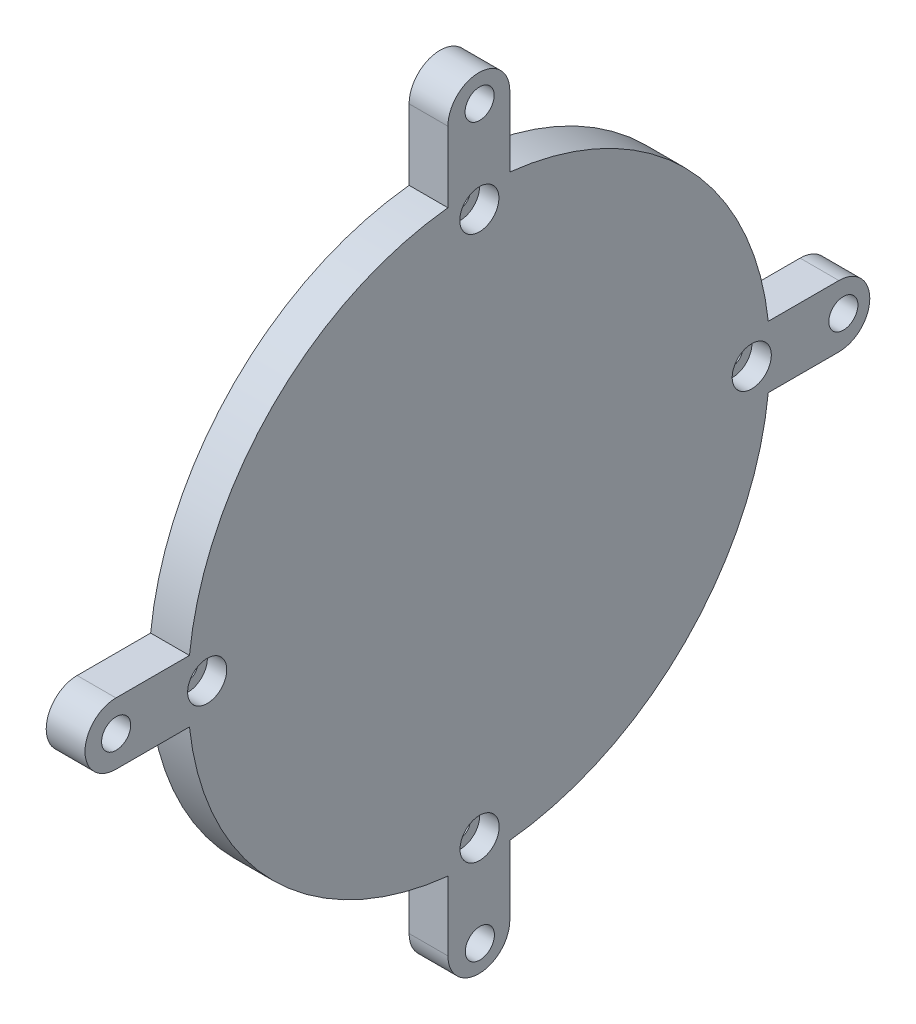
SolidWorks part; units mm, degrees
ref_plane "Front Plane" through (0, 0, 0) normal (1, 0, 0) x (0, 1, 0)
ref_plane "Top Plane" through (0, 0, 0) normal (0, 0, 1) x (0, 1, 0)
ref_plane "Right Plane" through (0, 0, 0) normal (0, 1, 0) x (-1, 0, 0)
sketch "Sketch1" plane through (0, 0, 0) normal (1, 0, 0) x (0, 1, 0)
  circle A0 centre (0, 0) radius 75
  dimension "D1" = 150
extrude "Boss-Extrude1" add sketch "Sketch1" along normal blind 10
sketch "Sketch2" plane through (0, 0, 0) normal (-1, 0, 0) x (0, -1, 0)
  line L0 (-92.771, 0) -> (92.382, 0) construction
  line L1 (-92.771, 7.974) -> (92.382, 7.974)
  line L2 (-92.771, -7.974) -> (92.382, -7.974)
  line L3 (0, -92.7697) -> (0, 93.521) construction
  line L6 (-7.9683, -92.7697) -> (-7.9683, 93.521)
  line L7 (7.9683, -92.7697) -> (7.9683, 93.521)
  arc A0 (-92.771, 7.974) -> (-92.771, -7.974) centre (-92.771, 0) ccw
  arc A1 (92.382, -7.974) -> (92.382, 7.974) centre (92.382, 0) ccw
  arc A4 (-7.9683, -92.7697) -> (7.9683, -92.7697) centre (0, -92.7697) ccw
  arc A5 (7.9683, 93.521) -> (-7.9683, 93.521) centre (0, 93.521) ccw
  point P3 (-0.1945, 0)
  point P11 (0, 0.3757)
extrude "Boss-Extrude2" add sketch "Sketch2" against normal blind 10 contours L1 A1 L2 A0 | L6 A5 L7 A4
sketch "Sketch3" plane through (10, 0, 0) normal (1, 0, 0) x (0, 1, 0)
  circle A0 centre (0, 70) radius 2.5
  circle A1 centre (0, 93.4679) radius 3.75
  point P4 (0, 70)
  point P5 (0, 24.9741)
  point P7 (0, 93.521)
  point P10 (0, 93.521)
  point P11 (0, 93.4679)
  dimension "D1" = 7.5
  dimension "D2" = 5
  dimension "D3" = 70
extrude "Cut-Extrude1" cut sketch "Sketch3" against normal through all both and the other way through all
pattern_circular "CirPattern1" count 4 over 360 about axis through (0, 0.032, -0.2252) along (1, 0, 0) of "Cut-Extrude1"
sketch "Sketch4" plane through (10, 0, 0) normal (1, 0, 0) x (0, 1, 0)
  circle A0 centre (0, 70) radius 5.0436
  point P2 (0.4567, 65.9271)
  point P5 (0, 65.9271)
  point P6 (0, 65.9271)
  point P7 (0, 0)
  point P8 (5.3901, 36.2005)
  point P9 (0, 37.9151)
  dimension "D1" = 70
extrude "Cut-Extrude2" cut sketch "Sketch4" against normal blind 5 and the other way through all
pattern_circular "CirPattern2" count 4 over 360 about axis through (0, 0.032, -0.1572) along (1, 0, 0) of "Cut-Extrude2"
